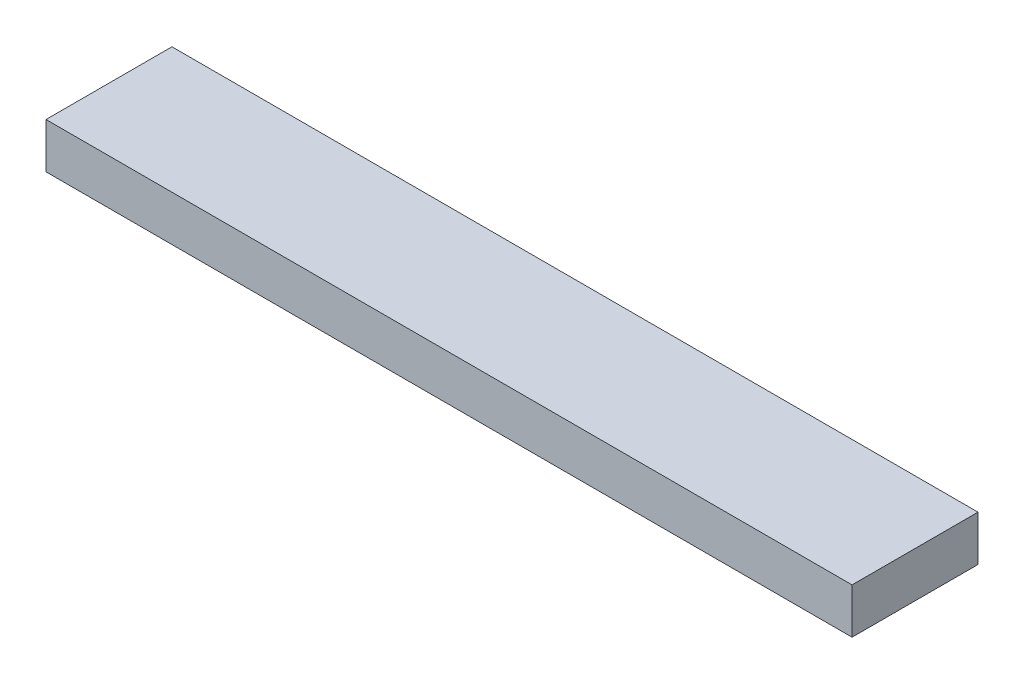
SolidWorks part; units mm, degrees
material "Perspex (TM) GS Acrylic Cast Sheet"
ref_plane "Front Plane" through (0, 0, 0) normal (0, 0, 1) x (1, 0, 0)
ref_plane "Top Plane" through (0, 0, 0) normal (0, 1, 0) x (1, 0, 0)
ref_plane "Right Plane" through (0, 0, 0) normal (1, 0, 0) x (0, 0, -1)
sketch "Sketch1" plane through (0, 0, 0) normal (0, 1, 0) x (1, 0, 0)
  line L1 (-40, -6.25) -> (40, -6.25)
  line L2 (-40, -6.25) -> (-40, 6.25)
  line L3 (-40, 6.25) -> (40, 6.25)
  line L4 (40, -6.25) -> (40, 6.25)
  line L5 (-40, -6.25) -> (40, 6.25) construction
  line L6 (-40, 6.25) -> (40, -6.25) construction
  point P0 (0, 0)
  point P1 (0, 0)
  dimension "D1" = 12.5
  dimension "D2" = 80
extrude "Boss-Extrude2" add sketch "Sketch1" along normal blind 4.5
sketch "Sketch3" plane through (0, 0, 0) normal (0, -1, 0) x (1, 0, 0)
  circle A0 centre (30, 0) radius 3.125
  dimension "D1" = 6.25
sketch "Sketch4" plane through (0, 0, 0) normal (0, -1, 0) x (1, 0, 0)
  line L0 (-40, -6.25) -> (-40, 6.25) construction
  circle A0 centre (-12, 0) radius 3.125
  dimension "D1" = 6.25
  dimension "D2" = 28
sketch "Sketch5" plane through (0, 4.5, 0) normal (0, 1, 0) x (1, 0, 0)
  circle A0 centre (30, 0) radius 3.125
  circle A1 centre (-12, 0) radius 3.125
